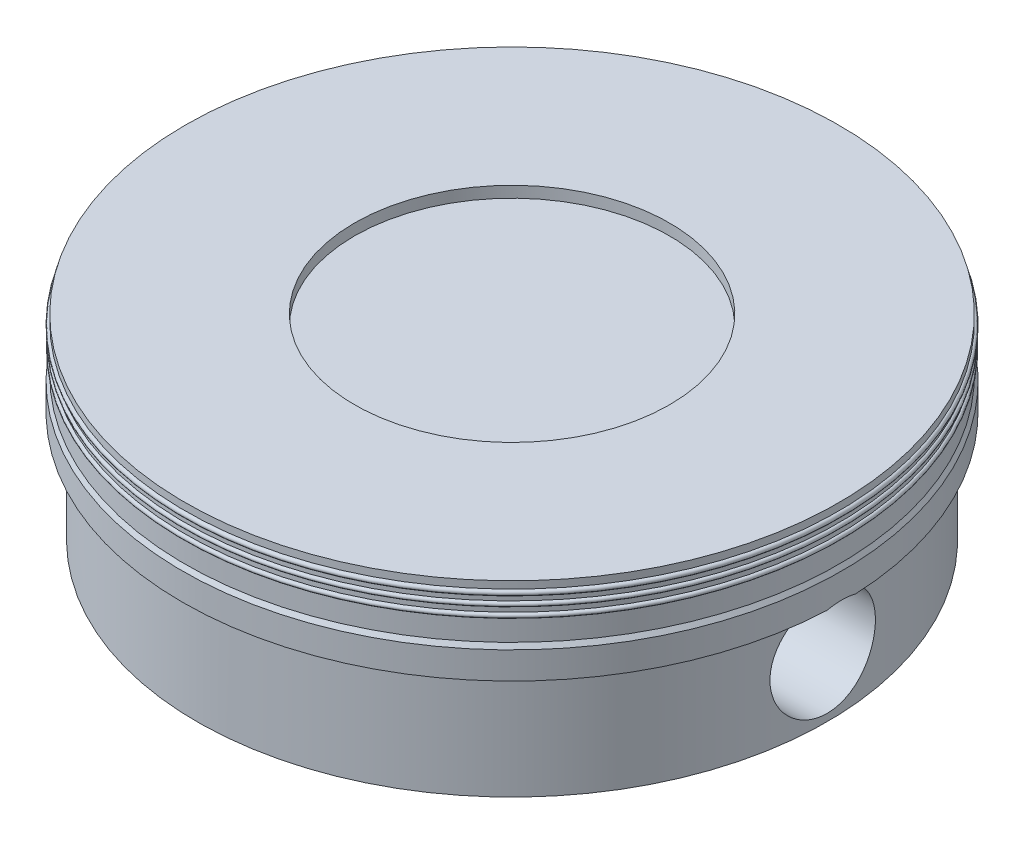
SolidWorks part; units mm, degrees
ref_plane "Front Plane" through (0, 0, 0) normal (0, 0, 1) x (1, 0, 0)
ref_plane "Top Plane" through (0, 0, 0) normal (0, 1, 0) x (1, 0, 0)
ref_plane "Right Plane" through (0, 0, 0) normal (1, 0, 0) x (0, 0, -1)
sketch "Sketch1" plane through (0, 0, 0) normal (0, 0, 1) x (1, 0, 0)
  line L0 (0, 3) -> (0, 0) construction
  line L1 (0, 0) -> (5, 0) construction
  line L2 (3.43, 0) -> (3.43, 1.93)
  line L3 (3.43, 1.93) -> (4.2, 1.93)
  line L4 (4.2, 1.93) -> (4.2, 2.33)
  line L5 (4.2, 2.33) -> (0, 2.33)
  line L6 (0, 2.33) -> (0, 2.8)
  line L7 (0, 2.8) -> (2.39, 2.8)
  line L8 (2.39, 2.8) -> (2.39, 2.97)
  line L9 (2.39, 2.97) -> (4.96, 2.97)
  line L10 (4.96, 2.97) -> (4.96, 2.8603)
  line L11 (4.96, 2.16) -> (5, 2.09)
  line L12 (5, 2.09) -> (5, 1.68)
  line L13 (5, 1.68) -> (4.78, 1.68)
  line L14 (4.78, 1.68) -> (4.78, 0)
  line L15 (4.78, 0) -> (3.43, 0)
  line L16 (4.96, 2.4836) -> (4.96, 2.16)
  line L17 (4.96, 2.6348) -> (4.96, 2.5564)
  line L18 (4.96, 2.7797) -> (4.96, 2.7052)
  arc A0 (4.96, 2.7797) -> (4.96, 2.8603) centre (4.96, 2.82) ccw
  arc A1 (4.96, 2.6348) -> (4.96, 2.7052) centre (4.96, 2.67) ccw
  arc A2 (4.96, 2.4836) -> (4.96, 2.5564) centre (4.96, 2.52) ccw
  dimension "D1" = 3
  dimension "D2" = 5
  dimension "D3" = 0.04
  dimension "D4" = 5
  dimension "D5" = 0.22
  dimension "D6" = 1.68
  dimension "D7" = 1.93
  dimension "D8" = 0.4
  dimension "D9" = 1.35
  dimension "D10" = 2.57
  dimension "D11" = 0.47
  dimension "D12" = 0.17
  dimension "D13" = 4.2
  dimension "D14" = 0.41
  dimension "D15" = 0.07
  dimension "D16" = 0.15
  dimension "D17" = 0.15
  dimension "D18" = 0.15
revolve "Revolve1" add sketch "Sketch1" angle 360 about L0
sketch "Sketch2" plane through (0, 0, 0) normal (0, -1, 0) x (1, 0, 0)
  line L0 (0, 3.43) -> (0, 0) construction
  line L1 (-1.75, 2.95) -> (-1.75, -2.95)
  line L2 (1.75, 2.95) -> (1.75, -2.95)
  circle A0 centre (0, 0) radius 3.43 construction
  arc A1 (-1.75, 2.95) -> (-1.75, -2.95) centre (0, 0) ccw
  arc A2 (1.75, -2.95) -> (1.75, 2.95) centre (0, 0) ccw
  dimension "D1" = 3.5
extrude "Boss-Extrude1" add sketch "Sketch2" against normal up to surface (2.33 mm away) up to face at (-4.2, 2.33, 0)
sketch "Sketch3" plane through (0, 0, 0) normal (1, 0, 0) x (0, 0, -1)
  circle A0 centre (0, 0.91) radius 0.8
  point P2 (0, 0)
  dimension "D1" = 1.6
  dimension "D2" = 0.91
extrude "Cut-Extrude1" cut sketch "Sketch3" against normal through all both and the other way through all
